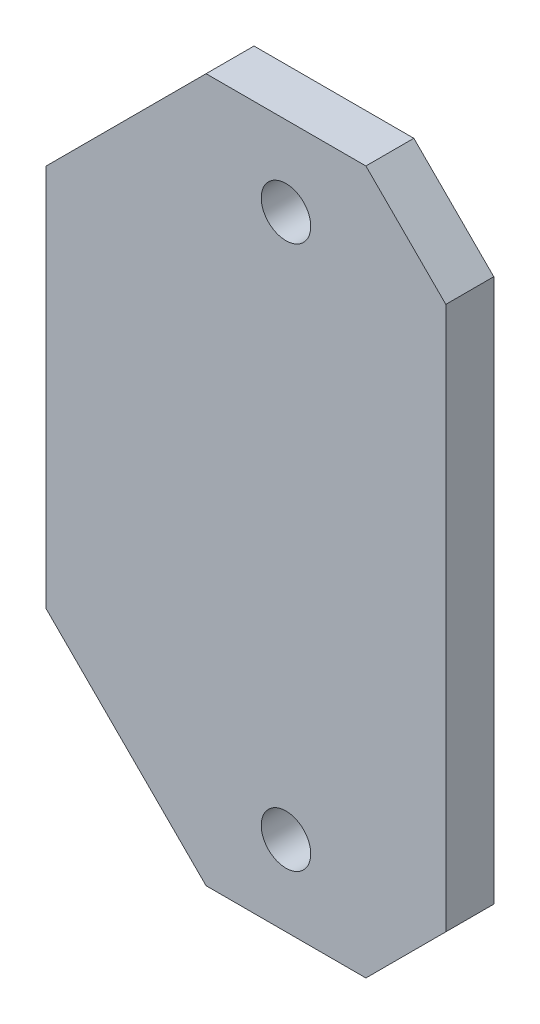
SolidWorks part; units mm, degrees
ref_plane "Front Plane" through (0, 0, 0) normal (0, 0, 1) x (1, 0, 0)
ref_plane "Top Plane" through (0, 0, 0) normal (0, 1, 0) x (1, 0, 0)
ref_plane "Right Plane" through (0, 0, 0) normal (1, 0, 0) x (0, 0, -1)
sketch "Sketch1" plane through (0, 0, 0) normal (0, 0, 1) x (1, 0, 0)
  line L1 (-11.6276, 19.952) -> (13.3724, 19.952)
  line L2 (-11.6276, 19.952) -> (-11.6276, -24.048)
  line L3 (-11.6276, -24.048) -> (13.3724, -24.048)
  line L4 (13.3724, 19.952) -> (13.3724, -24.048)
  dimension "D1" = 44
  dimension "D2" = 25
extrude "Boss-Extrude1" add sketch "Sketch1" along normal blind 3
chamfer "Chamfer1" distance 10 angle 45 2 edges at (-11.6276, -24.048, 1.5) (-11.6276, 19.952, 1.5)
chamfer "Chamfer2" distance 5 angle 45 2 edges at (13.3724, -24.048, 1.5) (13.3724, 19.952, 1.5)
sketch "Sketch2" plane through (0, 0, 3) normal (0, 0, 1) x (1, 0, 0)
  line L0 (8.3724, 19.952) -> (-1.6276, 19.952) construction
  line L1 (-1.6276, -24.048) -> (8.3724, -24.048) construction
  circle A0 centre (3.3724, 14.952) radius 1.55
  circle A1 centre (3.3724, -19.048) radius 1.55
  dimension "D1" = 3.1
  dimension "D2" = 3.1
  dimension "D3" = 5
  dimension "D4" = 5
extrude "Cut-Extrude1" cut sketch "Sketch2" against normal blind 3
